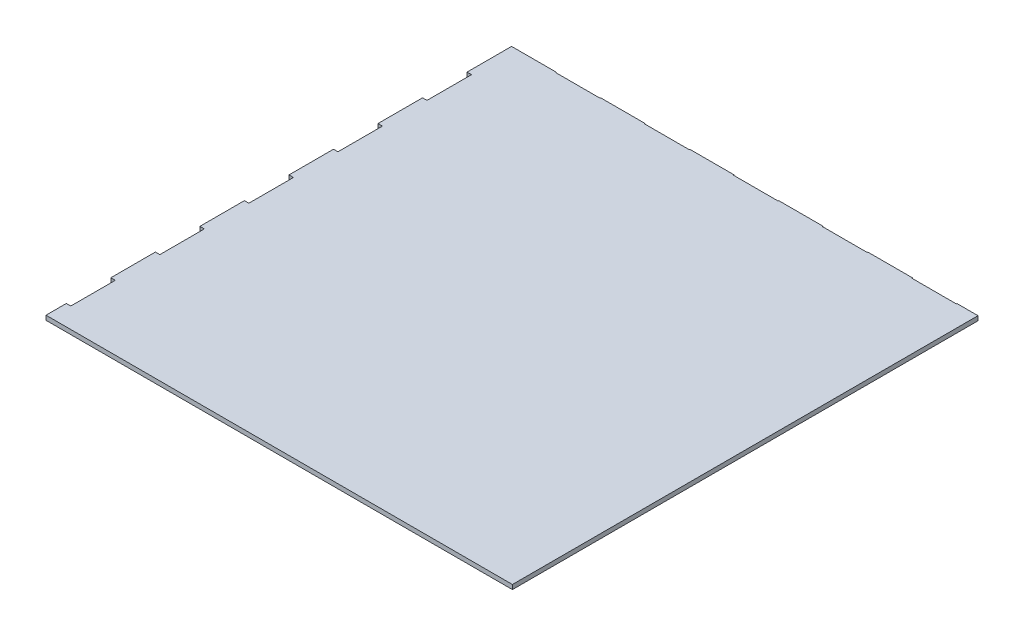
SolidWorks part; units mm, degrees
ref_plane "Front Plane" through (0, 0, 0) normal (0, 0, 1) x (1, 0, 0)
ref_plane "Top Plane" through (0, 0, 0) normal (0, 1, 0) x (1, 0, 0)
ref_plane "Right Plane" through (0, 0, 0) normal (1, 0, 0) x (0, 0, -1)
sketch "Sketch1" plane through (0, 0, 0) normal (0, 1, 0) x (1, 0, 0)
  line L1 (-315, -315) -> (315, -315)
  line L2 (-315, -315) -> (-315, 315)
  line L3 (-315, 315) -> (315, 315)
  line L4 (315, -315) -> (315, 315)
  line L5 (0, 315) -> (0, -315) construction
  line L6 (-315, 0) -> (315, 0) construction
  point P0 (0, 0)
extrude "Boss-Extrude1" add sketch "Sketch1" along normal blind 3
ref_plane "Plane1" through (0, 0, 285) normal (0, 0, 1) x (1, 0, 0)
sketch "Sketch3" plane through (0, 3, 0) normal (0, 1, 0) x (1, 0, 0)
  line L0 (-315, 315) -> (-315, -315) construction
  line L1 (-315, -285.0068) -> (-312, -285.0068)
  line L2 (-315, -285.0068) -> (-315, -255.0068)
  line L3 (-315, -255.0068) -> (-312, -255.0068)
  line L4 (-312, -285.0068) -> (-312, -255.0068)
  dimension "D1" = 30
  dimension "D2" = 3
extrude "Cut-Extrude2" cut sketch "Sketch3" against normal blind 3
pattern_linear "LPattern2" count 10 spacing 60 along (0, 0, -1) of "Cut-Extrude2"
ref_plane "Plane2" through (-0.72, 0, 0) normal (1, 0, 0) x (0, 0, -1)
mirror "Mirror1" about plane through (-0.72, 0, 0) normal (1, 0, 0) of "LPattern2", "Cut-Extrude2"
ref_plane "Plane3" through (-285, 0, 0) normal (-1, 0, 0) x (0, 0, 1)
sketch "Sketch5" plane through (0, 3, 0) normal (0, 1, 0) x (1, 0, 0)
  line L0 (-315, -315) -> (315, -315) construction
  line L1 (-285.0003, -315) -> (-255.0003, -315)
  line L2 (-285.0003, -315) -> (-285.0003, -312)
  line L3 (-285.0003, -312) -> (-255.0003, -312)
  line L4 (-255.0003, -315) -> (-255.0003, -312)
  dimension "D1" = 30
  dimension "D2" = 3
extrude "Cut-Extrude3" cut sketch "Sketch5" against normal blind 3
pattern_linear "LPattern3" count 10 spacing 60 along (1, 0, 0) of "Cut-Extrude3"
ref_plane "Plane4" through (0, 0, -1.29) normal (0, 0, 1) x (1, 0, 0)
mirror "Mirror2" about plane through (0, 0, -1.29) normal (0, 0, 1) of "LPattern3", "Cut-Extrude3"
other "SurfaceCut1"
other "SurfaceCut2"
